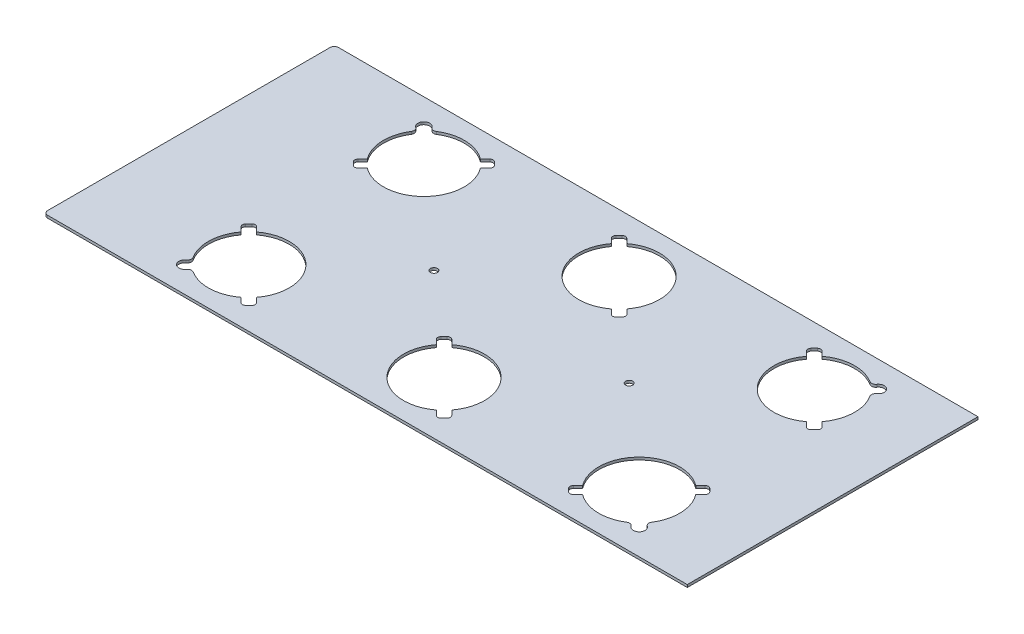
SolidWorks part; units mm, degrees
material "Hexcel AS4C (3000 Filaments)"
ref_plane "Front" through (0, 0, 0) normal (0, 0, 1) x (1, 0, 0)
ref_plane "Top" through (0, 0, 0) normal (0, 1, 0) x (1, 0, 0)
ref_plane "Right" through (0, 0, 0) normal (1, 0, 0) x (0, 0, -1)
sketch "Sketch1" plane through (0, 0, 0) normal (0, 1, 0) x (1, 0, 0)
  line L1 (-184.15, -88.9) -> (184.15, -88.9)
  line L2 (-184.15, -88.9) -> (-184.15, 88.9)
  line L3 (-184.15, 88.9) -> (184.15, 88.9)
  line L4 (184.15, -88.9) -> (184.15, 88.9)
  line L5 (-184.15, -88.9) -> (184.15, 88.9) construction
  line L6 (-184.15, 88.9) -> (184.15, -88.9) construction
  point P0 (0, 0)
  dimension "D1" = 368.3
  dimension "D2" = 177.8
extrude "Boss-Extrude1" add sketch "Sketch1" along normal blind 1.5748
sketch "Sketch2" plane through (-184.15, 0, 0) normal (-1, 0, 0) x (0, 0, 1)
  line L1 (88.9, 0) -> (-88.9, 0)
  line L2 (88.9, 0) -> (88.9, 1.5748)
  line L3 (88.9, 1.5748) -> (-88.9, 1.5748)
  line L4 (-88.9, 0) -> (-88.9, 1.5748)
extrude "Boss-Extrude2" add sketch "Sketch2" along normal blind 25.4
sketch "Sketch3" plane through (0, 0, 0) normal (0, -1, 0) x (1, 0, 0)
  line L0 (96.8413, -71.3316) -> (99.493, -68.6799) construction
  line L1 (141.9187, -35.7294) -> (139.267, -38.3811) construction
  line L2 (140.0095, -30.9918) -> (141.9187, -32.901) construction
  line L3 (134.5294, -33.6435) -> (137.1811, -30.9918) construction
  line L4 (104.2306, -73.4175) -> (101.5789, -76.0692) construction
  line L5 (98.7505, -76.0692) -> (96.8413, -74.16) construction
  line L6 (141.9187, -35.7294) -> (139.054, -38.5941)
  line L7 (140.0095, -30.9918) -> (141.9187, -32.901)
  line L8 (134.3164, -33.8565) -> (137.1811, -30.9918)
  line L9 (104.4436, -73.2045) -> (101.5789, -76.0692)
  line L10 (98.7505, -76.0692) -> (96.8413, -74.16)
  line L11 (96.8413, -71.3316) -> (99.706, -68.4669)
  line L12 (22.5387, -35.7294) -> (19.887, -38.3811) construction
  line L13 (20.6295, -30.9918) -> (22.5387, -32.901) construction
  line L14 (15.1494, -33.6435) -> (17.8011, -30.9918) construction
  line L15 (-22.5387, -71.3316) -> (-19.887, -68.6799) construction
  line L16 (-20.6295, -76.0692) -> (-22.5387, -74.16) construction
  line L17 (-15.1494, -73.4175) -> (-17.8011, -76.0692) construction
  line L18 (22.5387, -35.7294) -> (19.674, -38.5941)
  line L19 (20.6295, -30.9918) -> (22.5387, -32.901)
  line L20 (14.9364, -33.8565) -> (17.8011, -30.9918)
  line L21 (-22.5387, -71.3316) -> (-19.674, -68.4669)
  line L22 (-20.6295, -76.0692) -> (-22.5387, -74.16)
  line L23 (-14.9364, -73.2045) -> (-17.8011, -76.0692)
  line L24 (-137.1811, -30.9918) -> (-134.5294, -33.6435) construction
  line L25 (-141.9187, -32.901) -> (-140.0095, -30.9918) construction
  line L26 (-139.267, -38.3811) -> (-141.9187, -35.7294) construction
  line L27 (-99.493, -68.6799) -> (-96.8413, -71.3316) construction
  line L28 (-96.8413, -74.16) -> (-98.7505, -76.0692) construction
  line L29 (-101.5789, -76.0692) -> (-104.2306, -73.4175) construction
  line L30 (-137.1811, -30.9918) -> (-134.3164, -33.8565)
  line L31 (-141.9187, -32.901) -> (-140.0095, -30.9918)
  line L32 (-139.054, -38.5941) -> (-141.9187, -35.7294)
  line L33 (-99.706, -68.4669) -> (-96.8413, -71.3316)
  line L34 (-96.8413, -74.16) -> (-98.7505, -76.0692)
  line L35 (-101.5789, -76.0692) -> (-104.4436, -73.2045)
  line L36 (-134.5294, 33.6435) -> (-137.1811, 30.9918) construction
  line L37 (-140.0095, 30.9918) -> (-141.9187, 32.901) construction
  line L38 (-141.9187, 35.7294) -> (-139.267, 38.3811) construction
  line L39 (-96.8413, 71.3316) -> (-99.493, 68.6799) construction
  line L40 (-98.7505, 76.0692) -> (-96.8413, 74.16) construction
  line L41 (-104.2306, 73.4175) -> (-101.5789, 76.0692) construction
  line L42 (-134.3164, 33.8565) -> (-137.1811, 30.9918)
  line L43 (-140.0095, 30.9918) -> (-141.9187, 32.901)
  line L44 (-141.9187, 35.7294) -> (-139.054, 38.5941)
  line L45 (-96.8413, 71.3316) -> (-99.706, 68.4669)
  line L46 (-98.7505, 76.0692) -> (-96.8413, 74.16)
  line L47 (-104.4436, 73.2045) -> (-101.5789, 76.0692)
  line L48 (15.1494, 73.4175) -> (17.8011, 76.0692) construction
  line L49 (20.6295, 76.0692) -> (22.5387, 74.16) construction
  line L50 (22.5387, 71.3316) -> (19.887, 68.6799) construction
  line L51 (-20.6295, 30.9918) -> (-22.5387, 32.901) construction
  line L52 (-15.1494, 33.6435) -> (-17.8011, 30.9918) construction
  line L53 (-22.5387, 35.7294) -> (-19.887, 38.3811) construction
  line L54 (14.9364, 73.2045) -> (17.8011, 76.0692)
  line L55 (20.6295, 76.0692) -> (22.5387, 74.16)
  line L56 (22.5387, 71.3316) -> (19.674, 68.4669)
  line L57 (-20.6295, 30.9918) -> (-22.5387, 32.901)
  line L58 (-14.9364, 33.8565) -> (-17.8011, 30.9918)
  line L59 (-22.5387, 35.7294) -> (-19.674, 38.5941)
  line L60 (101.5789, 76.0692) -> (104.2306, 73.4175) construction
  line L61 (96.8413, 74.16) -> (98.7505, 76.0692) construction
  line L62 (99.493, 68.6799) -> (96.8413, 71.3316) construction
  line L63 (139.267, 38.3811) -> (141.9187, 35.7294) construction
  line L64 (141.9187, 32.901) -> (140.0095, 30.9918) construction
  line L65 (137.1811, 30.9918) -> (134.5294, 33.6435) construction
  line L66 (101.5789, 76.0692) -> (104.4436, 73.2045)
  line L67 (96.8413, 74.16) -> (98.7505, 76.0692)
  line L68 (99.706, 68.4669) -> (96.8413, 71.3316)
  line L69 (139.054, 38.5941) -> (141.9187, 35.7294)
  line L70 (141.9187, 32.901) -> (140.0095, 30.9918)
  line L71 (137.1811, 30.9918) -> (134.3164, 33.8565)
  arc A0 (104.4436, -73.2045) -> (139.054, -38.5941) centre (119.38, -53.5305) ccw
  arc A2 (-14.9364, -73.2045) -> (19.674, -38.5941) centre (0, -53.5305) ccw
  arc A3 (-99.706, -68.4669) -> (-134.3164, -33.8565) centre (-119.38, -53.5305) ccw
  arc A4 (-134.3164, 33.8565) -> (-99.706, 68.4669) centre (-119.38, 53.5305) ccw
  arc A5 (-14.9364, 33.8565) -> (19.674, 68.4669) centre (0, 53.5305) ccw
  arc A6 (139.054, 38.5941) -> (104.4436, 73.2045) centre (119.38, 53.5305) ccw
  arc A7 (96.8413, -71.3316) -> (96.8413, -74.16) centre (98.2555, -72.7458) ccw construction
  arc A8 (141.9187, -35.7294) -> (141.9187, -32.901) centre (140.5045, -34.3152) ccw construction
  arc A9 (140.0095, -30.9918) -> (137.1811, -30.9918) centre (138.5953, -32.406) ccw construction
  arc A10 (98.7505, -76.0692) -> (101.5789, -76.0692) centre (100.1647, -74.655) ccw construction
  arc A11 (141.9187, -35.7294) -> (141.9187, -32.901) centre (140.5045, -34.3152) ccw
  arc A12 (140.0095, -30.9918) -> (137.1811, -30.9918) centre (138.5953, -32.406) ccw
  arc A13 (98.7505, -76.0692) -> (101.5789, -76.0692) centre (100.1647, -74.655) ccw
  arc A14 (96.8413, -71.3316) -> (96.8413, -74.16) centre (98.2555, -72.7458) ccw
  arc A15 (134.3164, -33.8565) -> (99.706, -68.4669) centre (119.38, -53.5305) ccw
  arc A16 (22.5387, -35.7294) -> (22.5387, -32.901) centre (21.1245, -34.3152) ccw construction
  arc A17 (20.6295, -30.9918) -> (17.8011, -30.9918) centre (19.2153, -32.406) ccw construction
  arc A18 (-22.5387, -71.3316) -> (-22.5387, -74.16) centre (-21.1245, -72.7458) ccw construction
  arc A19 (-20.6295, -76.0692) -> (-17.8011, -76.0692) centre (-19.2153, -74.655) ccw construction
  arc A20 (22.5387, -35.7294) -> (22.5387, -32.901) centre (21.1245, -34.3152) ccw
  arc A21 (20.6295, -30.9918) -> (17.8011, -30.9918) centre (19.2153, -32.406) ccw
  arc A22 (-22.5387, -71.3316) -> (-22.5387, -74.16) centre (-21.1245, -72.7458) ccw
  arc A23 (-20.6295, -76.0692) -> (-17.8011, -76.0692) centre (-19.2153, -74.655) ccw
  arc A24 (14.9364, -33.8565) -> (-19.674, -68.4669) centre (0, -53.5305) ccw
  arc A25 (-137.1811, -30.9918) -> (-140.0095, -30.9918) centre (-138.5953, -32.406) ccw construction
  arc A26 (-141.9187, -32.901) -> (-141.9187, -35.7294) centre (-140.5045, -34.3152) ccw construction
  arc A27 (-96.8413, -74.16) -> (-96.8413, -71.3316) centre (-98.2555, -72.7458) ccw construction
  arc A28 (-101.5789, -76.0692) -> (-98.7505, -76.0692) centre (-100.1647, -74.655) ccw construction
  arc A29 (-137.1811, -30.9918) -> (-140.0095, -30.9918) centre (-138.5953, -32.406) ccw
  arc A30 (-141.9187, -32.901) -> (-141.9187, -35.7294) centre (-140.5045, -34.3152) ccw
  arc A31 (-96.8413, -74.16) -> (-96.8413, -71.3316) centre (-98.2555, -72.7458) ccw
  arc A32 (-101.5789, -76.0692) -> (-98.7505, -76.0692) centre (-100.1647, -74.655) ccw
  arc A33 (-140.0095, 30.9918) -> (-137.1811, 30.9918) centre (-138.5953, 32.406) ccw construction
  arc A34 (-141.9187, 35.7294) -> (-141.9187, 32.901) centre (-140.5045, 34.3152) ccw construction
  arc A35 (-96.8413, 71.3316) -> (-96.8413, 74.16) centre (-98.2555, 72.7458) ccw construction
  arc A36 (-98.7505, 76.0692) -> (-101.5789, 76.0692) centre (-100.1647, 74.655) ccw construction
  arc A37 (-140.0095, 30.9918) -> (-137.1811, 30.9918) centre (-138.5953, 32.406) ccw
  arc A38 (-141.9187, 35.7294) -> (-141.9187, 32.901) centre (-140.5045, 34.3152) ccw
  arc A39 (-96.8413, 71.3316) -> (-96.8413, 74.16) centre (-98.2555, 72.7458) ccw
  arc A40 (-98.7505, 76.0692) -> (-101.5789, 76.0692) centre (-100.1647, 74.655) ccw
  arc A41 (20.6295, 76.0692) -> (17.8011, 76.0692) centre (19.2153, 74.655) ccw construction
  arc A42 (22.5387, 71.3316) -> (22.5387, 74.16) centre (21.1245, 72.7458) ccw construction
  arc A43 (-22.5387, 35.7294) -> (-22.5387, 32.901) centre (-21.1245, 34.3152) ccw construction
  arc A44 (-20.6295, 30.9918) -> (-17.8011, 30.9918) centre (-19.2153, 32.406) ccw construction
  arc A45 (20.6295, 76.0692) -> (17.8011, 76.0692) centre (19.2153, 74.655) ccw
  arc A46 (22.5387, 71.3316) -> (22.5387, 74.16) centre (21.1245, 72.7458) ccw
  arc A47 (-22.5387, 35.7294) -> (-22.5387, 32.901) centre (-21.1245, 34.3152) ccw
  arc A48 (-20.6295, 30.9918) -> (-17.8011, 30.9918) centre (-19.2153, 32.406) ccw
  arc A49 (101.5789, 76.0692) -> (98.7505, 76.0692) centre (100.1647, 74.655) ccw construction
  arc A50 (96.8413, 74.16) -> (96.8413, 71.3316) centre (98.2555, 72.7458) ccw construction
  arc A51 (141.9187, 32.901) -> (141.9187, 35.7294) centre (140.5045, 34.3152) ccw construction
  arc A52 (137.1811, 30.9918) -> (140.0095, 30.9918) centre (138.5953, 32.406) ccw construction
  arc A53 (101.5789, 76.0692) -> (98.7505, 76.0692) centre (100.1647, 74.655) ccw
  arc A54 (96.8413, 74.16) -> (96.8413, 71.3316) centre (98.2555, 72.7458) ccw
  arc A55 (141.9187, 32.901) -> (141.9187, 35.7294) centre (140.5045, 34.3152) ccw
  arc A56 (137.1811, 30.9918) -> (140.0095, 30.9918) centre (138.5953, 32.406) ccw
  arc A58 (-104.4436, 73.2045) -> (-139.054, 38.5941) centre (-119.38, 53.5305) ccw
  arc A59 (14.9364, 73.2045) -> (-19.674, 38.5941) centre (0, 53.5305) ccw
  arc A60 (99.706, 68.4669) -> (134.3164, 33.8565) centre (119.38, 53.5305) ccw
  arc A61 (-139.054, -38.5941) -> (-104.4436, -73.2045) centre (-119.38, -53.5305) ccw
  point P118 (0, 0)
  point P128 (-139.054, -38.5941)
  point P130 (-104.4436, -73.2045)
  dimension "D1" = 24.7015
extrude "Cut-Extrude1" cut sketch "Sketch3" against normal through all
hole_wizard "9/32 (0.28125) Diameter Hole1" positions "Sketch4" profile "Sketch5" hole size "9/32" standard "ANSI Inch" end condition through all
sketch "Sketch4" plane through (0, 0, 0) normal (0, -1, 0) x (-1, 0, 0)
  point P0 (-139.0015, 73.152)
  point P3 (139.0015, 73.152)
  point P6 (139.0015, -73.152)
  point P9 (-139.0015, -73.152)
sketch "Sketch5" plane through (139.0015, 0, -73.152) normal (1, 0, 0) x (0, 0, -1)
  line L0 (0, 0) -> (0, 1.5748)
  line L1 (0, 1.5748) -> (3.5719, 1.5748)
  line L2 (3.5719, 1.5748) -> (3.5719, 0)
  line L5 (3.5719, 0) -> (0, 0)
  line L11 (0, -6.35) -> (0, 107.95) construction
  dimension "Thru Hole Dia." = 7.1437
  dimension "Thru Hole Depth" = 1.5748
fillet "Fillet1" radius 2.54 10 edges at (-209.55, 0.7874, -88.9) (-209.55, 0.7874, 88.9) (-135.5602, 0.7874, 72.195) (-138.0445, 0.7874, 69.7107) (-138.0445, 0.7874, -69.7107) (-135.5602, 0.7874, -72.195) (135.5602, 0.7874, -72.195) (138.0445, 0.7874, -69.7107) (138.0445, 0.7874, 69.7107) (135.5602, 0.7874, 72.195)
hole_wizard "#8 Clearance Hole1" positions "Sketch6" profile "Sketch7" hole size "#8" standard "ANSI Inch" end condition through all
sketch "Sketch6" plane through (0, 0, 0) normal (0, -1, 0) x (-1, 0, 0)
  point P0 (-59.69, 0)
  point P3 (59.69, 0)
sketch "Sketch7" plane through (59.69, 0, 0) normal (1, 0, 0) x (0, 0, -1)
  line L0 (0, 0) -> (0, 1.5748)
  line L1 (0, 1.5748) -> (2.1526, 1.5748)
  line L2 (2.1526, 1.5748) -> (2.1526, 0)
  line L5 (2.1526, 0) -> (0, 0)
  line L11 (0, -6.35) -> (0, 107.95) construction
  dimension "Thru Hole Dia." = 4.3053
  dimension "Thru Hole Depth" = 1.5748
